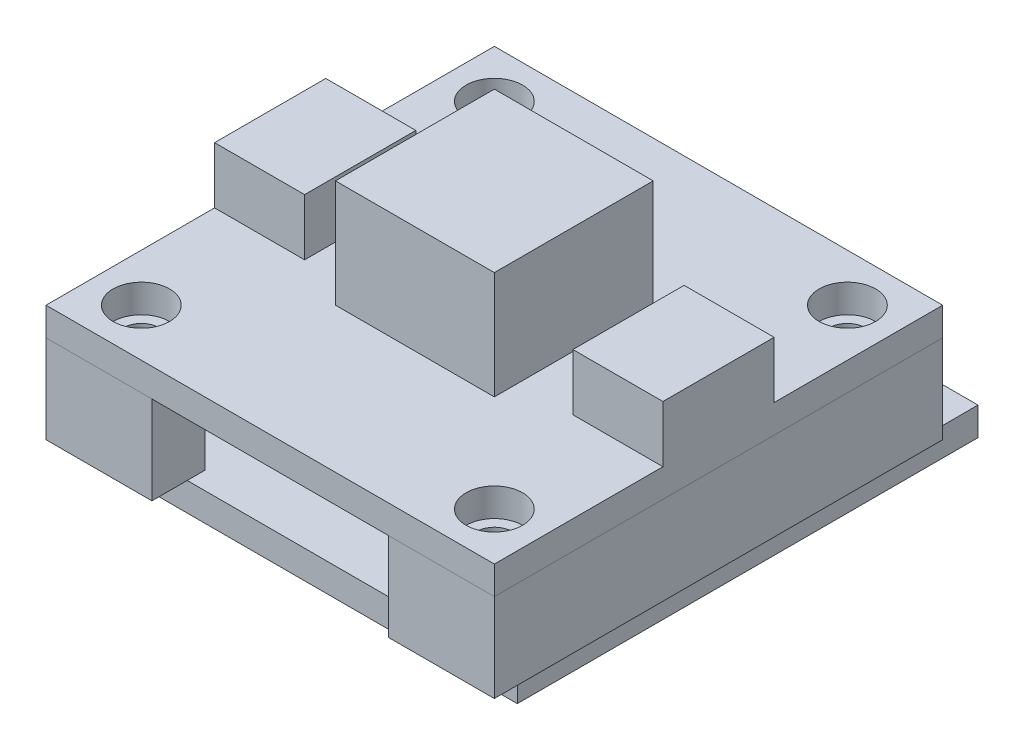
SolidWorks part; units mm, degrees
ref_plane "Front Plane" through (0, 0, 0) normal (0, 0, 1) x (1, 0, 0)
ref_plane "Top Plane" through (0, 0, 0) normal (0, 1, 0) x (1, 0, 0)
ref_plane "Right Plane" through (0, 0, 0) normal (1, 0, 0) x (0, 0, -1)
sketch "Sketch1" plane through (0, 0, 0) normal (0, 1, 0) x (1, 0, 0)
  line L1 (-12.7, -12.7) -> (12.7, -12.7)
  line L2 (-12.7, -12.7) -> (-12.7, 12.7)
  line L3 (-12.7, 12.7) -> (12.7, 12.7)
  line L4 (12.7, -12.7) -> (12.7, 12.7)
  line L5 (-12.7, -12.7) -> (12.7, 12.7) construction
  line L6 (-12.7, 12.7) -> (12.7, -12.7) construction
  line L7 (-10, -10) -> (10, -10) construction
  line L8 (-10, -10) -> (-10, 10) construction
  line L9 (-10, 10) -> (10, 10) construction
  line L10 (10, -10) -> (10, 10) construction
  line L11 (-10, -10) -> (10, 10) construction
  line L12 (-10, 10) -> (10, -10) construction
  circle A0 centre (-10, 10) radius 1.6
  circle A1 centre (10, 10) radius 1.6
  circle A2 centre (10, -10) radius 1.6
  circle A3 centre (-10, -10) radius 1.6
  point P0 (0, 0)
  point P5 (0, 0)
  dimension "D3" = 3.2
  dimension "D1" = 25.4
  dimension "D2" = 20
extrude "Boss-Extrude1" add sketch "Sketch1" along normal blind 1.6
sketch "Sketch2" plane through (0, 1.6, 0) normal (0, 1, 0) x (1, 0, 0)
  line L1 (-4.5, -4.5) -> (4.5, -4.5)
  line L2 (-4.5, -4.5) -> (-4.5, 4.5)
  line L3 (-4.5, 4.5) -> (4.5, 4.5)
  line L4 (4.5, -4.5) -> (4.5, 4.5)
  line L5 (-4.5, -4.5) -> (4.5, 4.5) construction
  line L6 (-4.5, 4.5) -> (4.5, -4.5) construction
  point P0 (0, 0)
  dimension "D1" = 9
extrude "Boss-Extrude2" add sketch "Sketch2" along normal blind 6.1
sketch "Sketch3" plane through (0, 1.6, 0) normal (0, 1, 0) x (1, 0, 0)
  line L0 (-12.7, 0) -> (12.7, 0) construction
  line L1 (-12.7, 12.7) -> (-12.7, -12.7) construction
  line L2 (12.7, -12.7) -> (12.7, 12.7) construction
  line L4 (-12.7, -3.15) -> (-7.6, -3.15)
  line L5 (-12.7, -3.15) -> (-12.7, 3.15)
  line L6 (-12.7, 3.15) -> (-7.6, 3.15)
  line L7 (-7.6, -3.15) -> (-7.6, 3.15)
  line L8 (-12.7, -3.15) -> (-7.6, 3.15) construction
  line L9 (-12.7, 3.15) -> (-7.6, -3.15) construction
  line L10 (7.6, -3.15) -> (12.7, -3.15)
  line L11 (7.6, -3.15) -> (7.6, 3.15)
  line L12 (7.6, 3.15) -> (12.7, 3.15)
  line L13 (12.7, -3.15) -> (12.7, 3.15)
  line L14 (7.6, -3.15) -> (12.7, 3.15) construction
  line L15 (7.6, 3.15) -> (12.7, -3.15) construction
  point P6 (-10.15, 0)
  point P11 (10.15, 0)
  point P16 (-12.7, 3.85)
  dimension "D1" = 5.1
  dimension "D2" = 6.3
extrude "Boss-Extrude3" add sketch "Sketch3" along normal blind 3.2
ref_plane "Plane1" through (0, -5, 0) normal (0, -1, 0) x (-1, 0, 0)
sketch "Sketch4" plane through (0, -5, 0) normal (0, -1, 0) x (-1, 0, 0)
  line L0 (0, 0) -> (0, 2.35) construction
  line L2 (-12, -10.7) -> (12, -10.7)
  line L3 (-12, -10.7) -> (-12, 15.4)
  line L4 (-12, 15.4) -> (12, 15.4)
  line L5 (12, -10.7) -> (12, 15.4)
  line L6 (-12, -10.7) -> (12, 15.4) construction
  line L7 (-12, 15.4) -> (12, -10.7) construction
  line L8 (12.7, -12.7) -> (-12.7, -12.7) construction
  dimension "D1" = 26.1
  dimension "D2" = 2
  dimension "D3" = 24
extrude "Boss-Extrude4" add sketch "Sketch4" along normal blind 1.6 separate body
sketch "Sketch5" plane through (0, -6.6, 0) normal (0, -1, 0) x (1, 0, 0)
  line L0 (-10, -10) -> (10, -10) construction
  line L1 (-9, -5.9) -> (0, 0) construction
  line L2 (0, 0) -> (9, -5.9) construction
  line L3 (-9, -5.9) -> (9, -5.9) construction
  line L4 (-12, -15.4) -> (12, -15.4) construction
  circle A0 centre (-10, -10) radius 1.6 construction
  circle A1 centre (-10, -10) radius 1.6 construction
  circle A2 centre (10, -10) radius 1.6 construction
  circle A3 centre (10, -10) radius 1.6 construction
  circle A4 centre (-9, -5.9) radius 1.6
  circle A5 centre (9, -5.9) radius 1.6
  dimension "D1" = 3.2
  dimension "D2" = 18
  dimension "D3" = 9.5
extrude "Cut-Extrude1" cut sketch "Sketch5" against normal blind 1.6
sketch "Sketch6" plane through (0, -6.6, 0) normal (0, -1, 0) x (1, 0, 0)
  line L0 (-12, -15.4) -> (12, -15.4) construction
  line L1 (-5.2, -15.4) -> (5.2, -15.4)
  line L2 (-5.2, -15.4) -> (-5.2, -9.2)
  line L3 (-5.2, -9.2) -> (5.2, -9.2)
  line L4 (5.2, -15.4) -> (5.2, -9.2)
  point P6 (0, -15.4)
  point P7 (0, -15.4)
  dimension "D1" = 10.4
  dimension "D2" = 6.2
extrude "Boss-Extrude5" add sketch "Sketch6" along normal blind 2.2
sketch "Sketch7" plane through (0, 0, 0) normal (0, -1, 0) x (1, 0, 0)
  line L0 (-12.7, 12.7) -> (-12.7, -12.7)
  line L1 (-12.7, -12.7) -> (-12.7, 12.7) construction
  line L2 (-12.7, -12.7) -> (-6.7, -12.7)
  line L3 (12.7, -12.7) -> (-12.7, -12.7) construction
  line L4 (-6.7, -12.7) -> (-6.7, 12.7)
  line L5 (-12.7, 12.7) -> (12.7, 12.7) construction
  line L6 (-6.7, 12.7) -> (-12.7, 12.7)
  line L7 (-6.7, 7.7) -> (6.7, 7.7)
  line L8 (12.7, 12.7) -> (6.7, 12.7)
  line L9 (12.7, 12.7) -> (12.7, -12.7)
  line L10 (12.7, -12.7) -> (6.7, -12.7)
  line L11 (6.7, 12.7) -> (6.7, -12.7)
  line L12 (-6.7, 4.7) -> (6.7, 4.7)
  line L13 (-6.7, -4.7) -> (6.7, -4.7)
  line L14 (-6.7, -7.7) -> (6.7, -7.7)
  circle A0 centre (-10, -10) radius 1.6 construction
  circle A1 centre (-10, -10) radius 1.6
  circle A2 centre (10, -10) radius 1.6 construction
  circle A3 centre (10, -10) radius 1.6
  circle A4 centre (-10, 10) radius 1.6 construction
  circle A5 centre (-10, 10) radius 1.6
  circle A6 centre (10, 10) radius 1.6 construction
  circle A7 centre (10, 10) radius 1.6
  circle M14 centre (10, 10) radius 1.6
  circle M15 centre (-10, -10) radius 1.6
  line M16 (12.7, -12.7) -> (12.7, 12.7)
  line M17 (12.7, 12.7) -> (-12.7, 12.7)
  line M18 (-12.7, 12.7) -> (-12.7, -12.7)
  line M19 (-12.7, -12.7) -> (12.7, -12.7)
  circle M20 centre (10, -10) radius 1.6
  circle M21 centre (-10, 10) radius 1.6
  dimension "D1" = 6
  dimension "D2" = 5
  dimension "D3" = 5
  dimension "D4" = 3
  dimension "D5" = 3
extrude "Boss-Extrude6" add sketch "Sketch7" along normal blind 1 separate body contours L11 M17 M19 M16 M20 M14 | L4 L12 L11 L7 | L4 L14 L11 L13 | L4 M19 M17 M18 M21 M15
sketch "Sketch8" plane through (0, -1, 0) normal (0, -1, 0) x (1, 0, 0)
  line L4 (-6.7, -4.7) -> (6.7, -4.7)
  line L5 (-6.7, 4.7) -> (-6.7, -4.7)
  line L6 (6.7, 4.7) -> (-6.7, 4.7)
  line L7 (6.7, -4.7) -> (6.7, 4.7)
  line L8 (-6.7, -4.7) -> (6.7, -4.7)
  line L9 (-6.7, 4.7) -> (-6.7, -4.7)
  line L10 (6.7, 4.7) -> (-6.7, 4.7)
  line L11 (6.7, -4.7) -> (6.7, 4.7)
  line L12 (12.7, 12.7) -> (6.7, 12.7)
  line L13 (6.7, 12.7) -> (6.7, 7.7)
  line L14 (6.7, 7.7) -> (-6.7, 7.7)
  line L15 (-6.7, 7.7) -> (-6.7, 12.7)
  line L16 (-6.7, 12.7) -> (-12.7, 12.7)
  line L17 (-12.7, 12.7) -> (-12.7, -12.7)
  line L18 (-12.7, -12.7) -> (-6.7, -12.7)
  line L19 (-6.7, -12.7) -> (-6.7, -7.7)
  line L20 (-6.7, -7.7) -> (6.7, -7.7)
  line L21 (6.7, -7.7) -> (6.7, -12.7)
  line L22 (6.7, -12.7) -> (12.7, -12.7)
  line L23 (12.7, -12.7) -> (12.7, 12.7)
  line L24 (12.7, 12.7) -> (6.7, 12.7)
  line L25 (6.7, 12.7) -> (6.7, 7.7)
  line L26 (6.7, 7.7) -> (-6.7, 7.7)
  line L27 (-6.7, 7.7) -> (-6.7, 12.7)
  line L28 (-6.7, 12.7) -> (-12.7, 12.7)
  line L29 (-12.7, 12.7) -> (-12.7, -12.7)
  line L30 (-12.7, -12.7) -> (-6.7, -12.7)
  line L31 (-6.7, -12.7) -> (-6.7, -7.7)
  line L32 (-6.7, -7.7) -> (6.7, -7.7)
  line L33 (6.7, -7.7) -> (6.7, -12.7)
  line L34 (6.7, -12.7) -> (12.7, -12.7)
  line L35 (12.7, -12.7) -> (12.7, 12.7)
  circle A0 centre (9, -5.9) radius 1.6 construction
  circle A1 centre (9, -5.9) radius 1.6
  circle A2 centre (-9, -5.9) radius 1.6 construction
  circle A3 centre (-9, -5.9) radius 1.6
  circle A6 centre (-10, 10) radius 2.1
  circle A7 centre (-10, 10) radius 2.1
  circle A9 centre (10, 10) radius 2.1
  circle A10 centre (10, 10) radius 2.1
  circle A12 centre (-10, -10) radius 2.1
  circle A13 centre (-10, -10) radius 2.1
  circle A15 centre (10, -10) radius 2.1
  circle A16 centre (10, -10) radius 2.1
  dimension "D4" = 4.2
  dimension "D1" = 0.5
  dimension "D2" = 0.5
  dimension "D3" = 0.5
  dimension "D5" = 0.5
  dimension "D6" = 0
  dimension "D7" = 0
extrude "Boss-Extrude7" add sketch "Sketch8" along normal up to surface (4 mm away) up to face at (-9, -5, -7.5)
sketch "Sketch9" plane through (0, -1, 0) normal (0, -1, 0) x (1, 0, 0)
  circle A0 centre (10, 10) radius 1
  circle A1 centre (-10, 10) radius 1
  circle A2 centre (-10, -10) radius 1
  circle A3 centre (10, -10) radius 1
  circle A4 centre (-10, 10) radius 1.6 construction
  circle A5 centre (-10, 10) radius 1.6
  circle A6 centre (10, 10) radius 1.6 construction
  circle A7 centre (10, 10) radius 1.6
  circle A8 centre (-10, -10) radius 1.6 construction
  circle A9 centre (-10, -10) radius 1.6
  circle A10 centre (10, -10) radius 1.6 construction
  circle A11 centre (10, -10) radius 1.6
  dimension "D1" = 2
extrude "Boss-Extrude8" add sketch "Sketch9" against normal up to surface (1 mm away) up to face at (0, 0, 0)
sketch "Sketch10" plane through (0, -5, 0) normal (0, -1, 0) x (1, 0, 0)
  circle A0 centre (-9, -5.9) radius 1
  circle A1 centre (9, -5.9) radius 1
  circle A2 centre (-9, -5.9) radius 1.6 construction
  circle A3 centre (-9, -5.9) radius 1.6
  circle A4 centre (9, -5.9) radius 1.6 construction
  circle A5 centre (9, -5.9) radius 1.6
  dimension "D1" = 2
extrude "Boss-Extrude9" add sketch "Sketch10" against normal up to surface (4 mm away) up to face at (-10, -1, 7.9)
sketch "Sketch11" plane through (0, 0, 0) normal (0, 1, 0) x (1, 0, 0)
  circle A0 centre (9, 5.9) radius 1 construction
  circle A1 centre (9, 5.9) radius 1
  circle A2 centre (-9, 5.9) radius 1 construction
  circle A3 centre (-9, 5.9) radius 1
  circle A4 centre (10, 10) radius 2.1 construction
  circle A5 centre (10, 10) radius 2.1 construction
  circle A6 centre (-10, 10) radius 2.1 construction
  circle A7 centre (-10, 10) radius 2.1 construction
  circle A8 centre (-9, 5.9) radius 2.1
  circle A9 centre (9, 5.9) radius 2.1
  dimension "D1" = 4.2
extrude "Cut-Extrude2" cut sketch "Sketch11" against normal blind 2 contours A1 | A3 | A8 A3 | A9 A1
sketch "Sketch12" plane through (0, -2, 0) normal (0, 1, 0) x (1, 0, 0)
  circle A0 centre (-9, 5.9) radius 1 construction
  circle A1 centre (-9, 5.9) radius 1
  circle A2 centre (9, 5.9) radius 1 construction
  circle A3 centre (9, 5.9) radius 1
extrude "Boss-Extrude10" add sketch "Sketch12" against normal blind 0.3
sketch "Sketch13" plane through (0, -5, 0) normal (0, -1, 0) x (1, 0, 0)
  line L1 (-6.7, 7.7) -> (6.7, 7.7)
  line L2 (-6.7, 7.7) -> (-6.7, -7.7)
  line L3 (-6.7, -7.7) -> (6.7, -7.7)
  line L4 (6.7, 7.7) -> (6.7, -7.7)
extrude "Cut-Extrude3" cut sketch "Sketch13" against normal blind 2
sketch "Sketch14" plane through (0, -3, 0) normal (0, -1, 0) x (1, 0, 0)
  line L0 (-6.7, 6.2) -> (6.7, 6.2) construction
  line L1 (-6.7, 7.7) -> (-6.7, 4.7) construction
  line L2 (6.7, 4.7) -> (6.7, 7.7) construction
  line L3 (-6.5, 6.2) -> (6.5, 6.2) construction
  line L4 (-6.5, 9.7) -> (6.5, 9.7)
  line L5 (-6.5, 2.7) -> (6.5, 2.7)
  arc A0 (-6.5, 9.7) -> (-6.5, 2.7) centre (-6.5, 6.2) ccw
  arc A1 (6.5, 2.7) -> (6.5, 9.7) centre (6.5, 6.2) ccw
  point P8 (0, 6.2)
  dimension "D2" = 20
  dimension "D1" = 7
extrude "Cut-Extrude4" cut sketch "Sketch14" along normal blind 11
